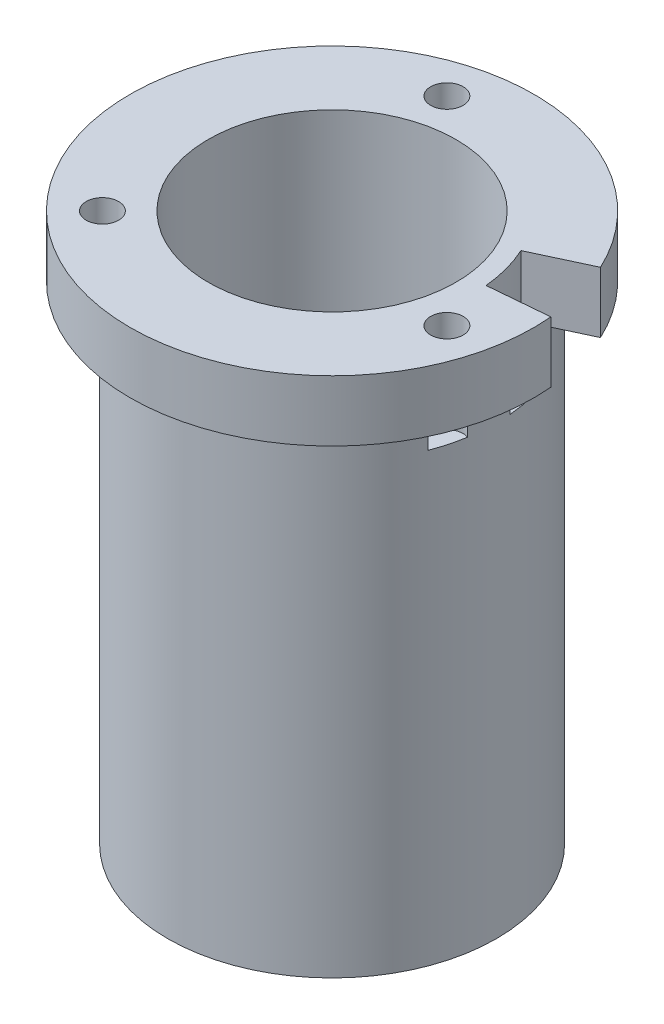
SolidWorks part; units mm, degrees
material "PTFE (general)"
ref_plane "Front Plane" through (0, 0, 0) normal (0, 0, 1) x (1, 0, 0)
ref_plane "Top Plane" through (0, 0, 0) normal (0, 1, 0) x (1, 0, 0)
ref_plane "Right Plane" through (0, 0, 0) normal (1, 0, 0) x (0, 0, -1)
sketch "Sketch2" plane through (0, 0, 0) normal (0, 0, 1) x (1, 0, 0)
  line L0 (0, 0) -> (6.1, 0) construction
  line L1 (6.1, 0) -> (8.1, 0)
  line L4 (8.1, 0) -> (8.1, 24)
  line L5 (8.1, 24) -> (9.95, 24)
  line L6 (9.95, 24) -> (9.95, 27)
  line L7 (9.95, 27) -> (6.1, 27)
  line L8 (6.1, 27) -> (6.1, 0)
  line L9 (0, 0) -> (0, 33.7258) construction
  dimension "D1" = 6.1
  dimension "D3" = 2
  dimension "D4" = 8.1
  dimension "D5" = 24
  dimension "D6" = 3.85
  dimension "D7" = 3
revolve "Revolve1" add sketch "Sketch2" angle 360 about L9
sketch "Sketch3" plane through (0, 27, 0) normal (0, 1, 0) x (1, 0, 0)
  line L0 (0, 0) -> (11.5633, 0) construction
  line L1 (0, 0) -> (13.3416, 1.1672) construction
  line L2 (0, 0) -> (9.0631, 4.2262) construction
  line L3 (6.3442, 2.9583) -> (9.0631, 4.2262)
  line L4 (6.9734, 0.6101) -> (9.9619, 0.8716)
  circle A0 centre (0, 0) radius 8 construction
  arc A1 (8, 0) -> (7.7274, -2.0706) centre (0, 0) cw construction
  circle A2 centre (7.7274, -2.0706) radius 0.8
  circle A3 centre (-5.6569, -5.6569) radius 0.8
  circle A4 centre (-2.0706, 7.7274) radius 0.8
  arc A5 (9.9619, 0.8716) -> (9.0631, 4.2262) centre (0, 0) ccw
  arc A6 (6.9734, 0.6101) -> (6.3442, 2.9583) centre (0, 0) ccw
  point P13 (0, 0)
  dimension "D1" = 3
  dimension "D3" = 20
  dimension "D4" = 7
  dimension "D2" = 5
extrude "Cut-Extrude1" cut sketch "Sketch3" against normal blind 5
equation "\"H\"=18.5"
equation "\"D\"= 15.5"
equation "\"OP_ANGLE\"= 120"
equation "\"D6@3DSketch6\" = \"R\""
equation "\"R\"= \"D\" / 2"
equation "\"D2@3DSketch6\" = \"D\""
equation "\"D8@3DSketch6\" = 18.5"
equation "\"D3@3DSketch6\" = \"H\""
equation "\"D15@3DSketch6\" = \"D\""
